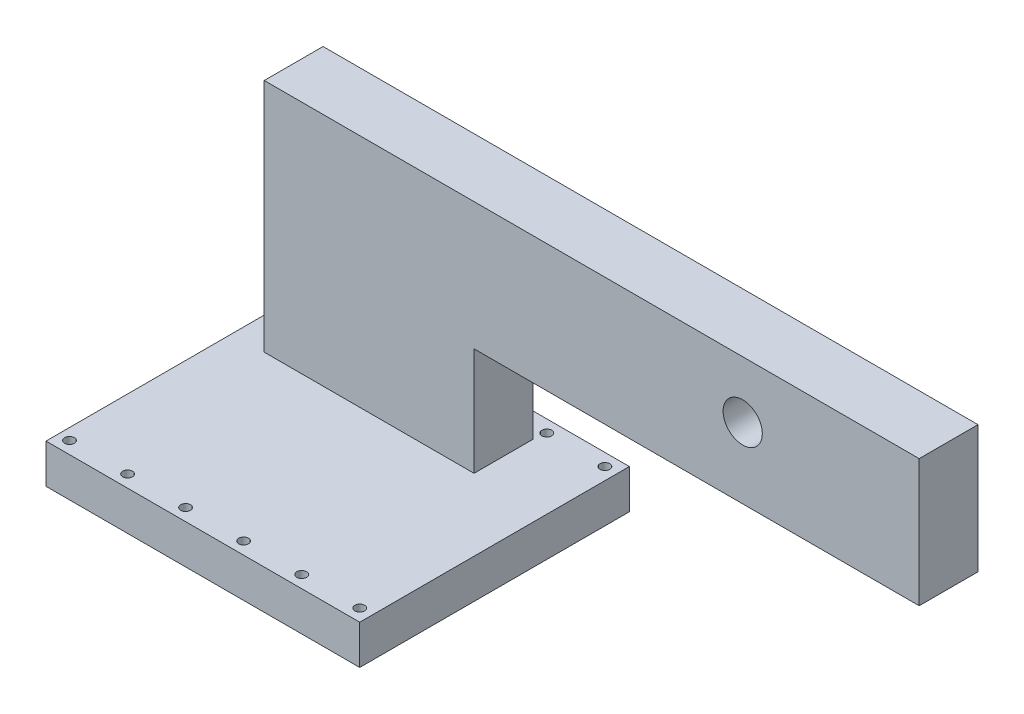
SolidWorks part; units mm, degrees
material "Aluminum Bronze"
ref_plane "Front Plane" through (0, 0, 0) normal (0, 0, 1) x (1, 0, 0)
ref_plane "Top Plane" through (0, 0, 0) normal (0, 1, 0) x (1, 0, 0)
ref_plane "Right Plane" through (0, 0, 0) normal (1, 0, 0) x (0, 0, -1)
sketch "Sketch1" plane through (0, 0, 0) normal (0, 0, 1) x (1, 0, 0)
  line L0 (0, 0) -> (0, 152.4)
  line L1 (0, 152.4) -> (424.18, 152.4)
  line L2 (424.18, 152.4) -> (424.18, 69.85)
  line L3 (424.18, 69.85) -> (135.89, 69.85)
  line L4 (135.89, 69.85) -> (135.89, 0)
  line L5 (135.89, 0) -> (0, 0)
other "Pen Sketch1" parameters "D1"=50.8085, "D2"=304.8, "D3"=110.5408, "D4"=67.4624
extrude "Boss-Extrude1" add sketch "Sketch1" along normal mid plane 38.1
sketch "Sketch2" plane through (0, 0, 19.05) normal (0, 0, 1) x (1, 0, 0)
  line L0 (424.18, 69.85) -> (424.18, 152.4) construction
  line L1 (424.18, 152.4) -> (0, 152.4) construction
  circle A0 centre (309.88, 115.57) radius 12.7
  dimension "D1" = 25.4
  dimension "D2" = 114.3
  dimension "D3" = 36.83
extrude "Cut-Extrude1" cut sketch "Sketch2" against normal through all
sketch "Sketch4" plane through (0, 0, 0) normal (0, -1, 0) x (1, 0, 0)
  line L0 (0, -19.05) -> (135.89, -19.05) construction
  line L1 (-20.828, 139.573) -> (182.372, 139.573)
  line L2 (-20.828, 139.573) -> (-20.828, -35.052)
  line L3 (-20.828, -35.052) -> (182.372, -35.052)
  line L4 (182.372, 139.573) -> (182.372, -35.052)
  line L5 (0, 19.05) -> (0, -19.05) construction
  line L6 (174.4345, -27.1145) -> (136.8425, -27.1145) construction
  circle A0 centre (174.4345, 131.6355) radius 3.175
  circle A1 centre (136.8425, 131.6355) radius 3.175
  circle A2 centre (99.2505, 131.6355) radius 3.175
  circle A3 centre (61.6585, 131.6355) radius 3.175
  circle A4 centre (24.0665, 131.6355) radius 3.175
  circle A5 centre (-13.5255, 131.6355) radius 3.175
  circle A6 centre (174.4345, -27.1145) radius 3.175
  circle A7 centre (136.8425, -27.1145) radius 3.175
  circle A8 centre (99.2505, -27.1145) radius 3.175
  circle A9 centre (61.6585, -27.1145) radius 3.175
  circle A10 centre (24.0665, -27.1145) radius 3.175
  circle A11 centre (-13.5255, -27.1145) radius 3.175
  dimension "D5" = 6.35
  dimension "D8" = 6.35
  dimension "D1" = 203.2
  dimension "D2" = 174.625
  dimension "D3" = 16.002
  dimension "D4" = 20.828
  dimension "D6" = 7.9375
  dimension "D7" = 7.9375
  dimension "D9" = 7.9375
  dimension "D10" = 7.9375
  dimension "D11" = 37.592
extrude "Boss-Extrude2" add sketch "Sketch4" along normal blind 25.4 separate body
